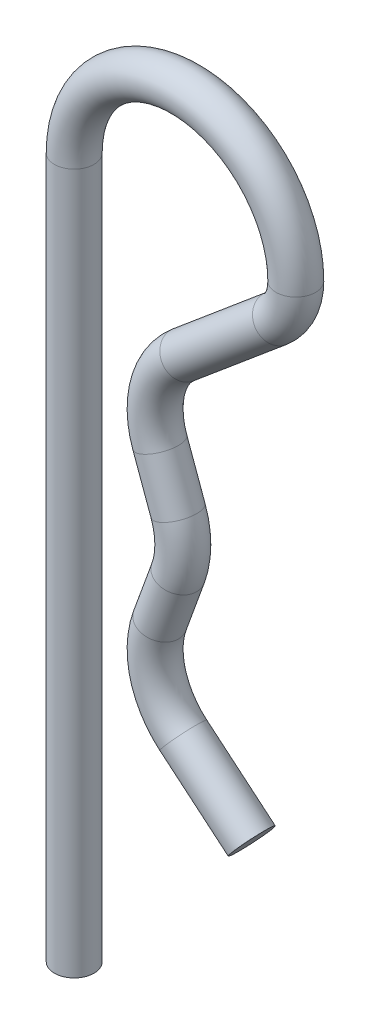
SolidWorks part; units mm, degrees
material "1.7014 (17CrS3)"
ref_plane "Płaszczyzna przednia" through (0, 0, 0) normal (0, 0, 1) x (1, 0, 0)
ref_plane "Płaszczyzna górna" through (0, 0, 0) normal (0, 1, 0) x (1, 0, 0)
ref_plane "Płaszczyzna prawa" through (0, 0, 0) normal (1, 0, 0) x (0, 0, -1)
ref_plane "Płaszczyzna1" through (0, -52.5, 0) normal (0, 1, 0) x (1, 0, 0)
sketch "Szkic1" plane through (0, -52.5, 0) normal (0, 1, 0) x (1, 0, 0)
  circle A0 centre (0, 0) radius 2.5
sketch "Szkic2" plane through (0, 0, 0) normal (0, 0, 1) x (1, 0, 0)
  line L0 (20.8215, -29.9759) -> (12.1857, -22.7296)
  line L1 (8.4744, -8.8788) -> (10.7723, -2.5652)
  line L2 (10.7723, 2.5652) -> (8.4744, 8.8788)
  line L3 (12.1857, 22.7296) -> (23.8925, 32.5528)
  line L4 (2.5, 36) -> (2.5, -52.5)
  arc A0 (8.4744, -8.8788) -> (12.1857, -22.7296) centre (20.2205, -13.154) ccw
  arc A1 (10.7723, -2.5652) -> (10.7723, 2.5652) centre (3.7246, 0) ccw
  arc A2 (8.4744, 8.8788) -> (12.1857, 22.7296) centre (20.2205, 13.154) cw
  arc A3 (23.8925, 32.5528) -> (25.5, 36) centre (21, 36) ccw
  arc A4 (25.5, 36) -> (2.5, 36) centre (14, 36) ccw
sweep "Wyciągnięcie po ścieżce1" add profiles "Szkic1" path "Szkic2"
